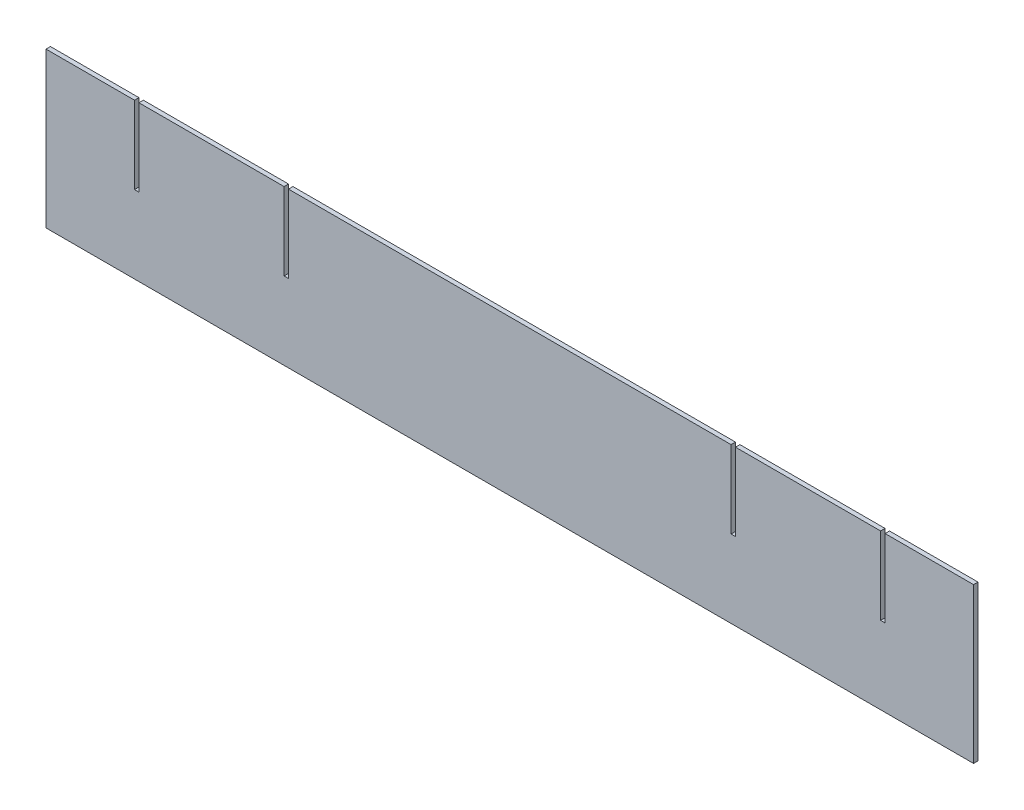
SolidWorks part; units mm, degrees
ref_plane "Front" through (0, 0, 0) normal (0, 0, 1) x (1, 0, 0)
ref_plane "Top" through (0, 0, 0) normal (0, 1, 0) x (1, 0, 0)
ref_plane "Right" through (0, 0, 0) normal (1, 0, 0) x (0, 0, -1)
sketch "草图1" plane through (0, 0, 0) normal (0, 0, 1) x (1, 0, 0)
  line L1 (-209.6, 35) -> (209.6, 35)
  line L2 (-209.6, 35) -> (-209.6, -35)
  line L3 (-209.6, -35) -> (209.6, -35)
  line L4 (209.6, 35) -> (209.6, -35)
  line L5 (-209.6, 35) -> (209.6, -35) construction
  line L6 (-209.6, -35) -> (209.6, 35) construction
  point P0 (0, 0)
  dimension "D1" = 70
  dimension "D2" = 419.2
extrude "凸台-拉伸1" add sketch "草图1" along normal blind 2
sketch "草图2" plane through (0, 0, 2) normal (0, 0, 1) x (1, 0, 0)
  line L0 (169.6, 35) -> (169.6, 0)
  line L1 (209.6, 35) -> (-209.6, 35) construction
  line L2 (102, 35) -> (102, 0)
  line L3 (-100, 35) -> (-100, 0)
  line L4 (-167.6, 35) -> (-167.6, 0)
  line L5 (209.6, -35) -> (209.6, 35) construction
  line L6 (169.6, 0) -> (167.6, 0)
  line L7 (167.6, 0) -> (167.6, 35)
  line L8 (167.6, 35) -> (169.6, 35)
  line L9 (102, 0) -> (100, 0)
  line L10 (100, 0) -> (100, 35)
  line L11 (100, 35) -> (102, 35)
  line L12 (-100, 0) -> (-102, 0)
  line L13 (-102, 0) -> (-102, 35)
  line L14 (-102, 35) -> (-100, 35)
  line L15 (-167.6, 0) -> (-169.6, 0)
  line L16 (-169.6, 0) -> (-169.6, 35)
  line L17 (-169.6, 35) -> (-167.6, 35)
  dimension "D1" = 40
  dimension "D2" = 65.6
  dimension "D3" = 2
  dimension "D4" = 2
  dimension "D5" = 200
  dimension "D6" = 2
  dimension "D7" = 65.6
  dimension "D8" = 2
extrude "切除-拉伸1" cut sketch "草图2" against normal blind 2
